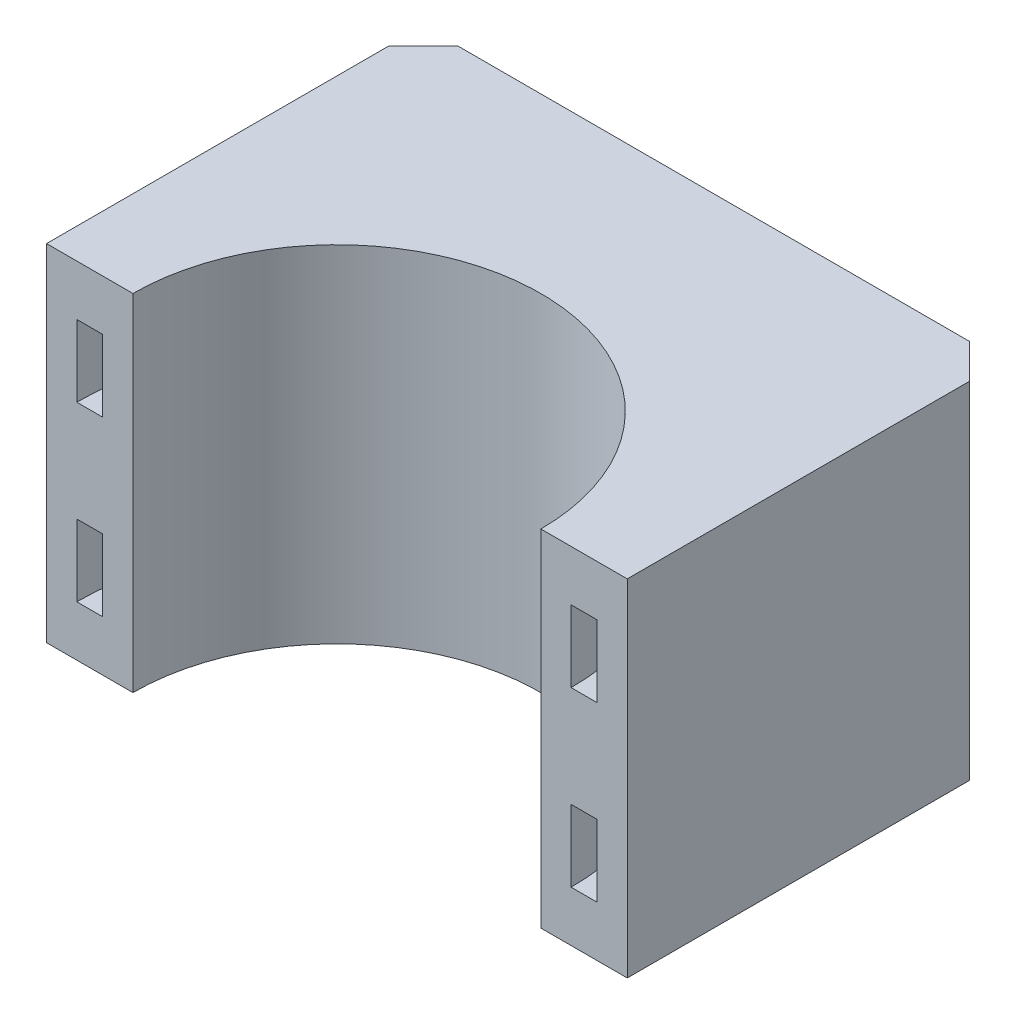
SolidWorks part; units mm, degrees
ref_plane "Front Plane" through (0, 0, 0) normal (0, 0, 1) x (1, 0, 0)
ref_plane "Top Plane" through (0, 0, 0) normal (0, 1, 0) x (1, 0, 0)
ref_plane "Right Plane" through (0, 0, 0) normal (1, 0, 0) x (0, 0, -1)
sketch "Sketch1" plane through (0, 0, 0) normal (0, 1, 0) x (1, 0, 0)
  line L0 (-11.8, 0) -> (-16.8, 0)
  line L1 (-16.8, 0) -> (-16.8, 21.8)
  line L2 (-16.8, 21.8) -> (16.8, 21.8)
  line L3 (16.8, 21.8) -> (16.8, 0)
  line L4 (16.8, 0) -> (11.8, 0)
  arc A0 (11.8, 0) -> (-11.8, 0) centre (0, 0) ccw
  point P7 (0, 11.8)
  dimension "D1" = 11.8
  dimension "D2" = 5
  dimension "D3" = 10
extrude "Boss-Extrude1" add sketch "Sketch1" along normal mid plane 20
sketch "Sketch2" plane through (0, 0, 0) normal (0, 0, 1) x (1, 0, 0)
  line L0 (0, 0) -> (0, -50000) construction
  line L1 (0, 0) -> (14.3, 0) construction
  line L2 (14.3, 5) -> (14.3, -5) construction
  line L3 (16.8, 0) -> (11.8, 0) construction
  line L5 (13.55, 7.075) -> (15.05, 7.075)
  line L6 (13.55, 7.075) -> (13.55, 2.925)
  line L7 (13.55, 2.925) -> (15.05, 2.925)
  line L8 (15.05, 7.075) -> (15.05, 2.925)
  line L9 (13.55, 7.075) -> (15.05, 2.925) construction
  line L10 (13.55, 2.925) -> (15.05, 7.075) construction
  line L11 (13.55, -2.925) -> (15.05, -2.925)
  line L12 (13.55, -2.925) -> (13.55, -7.075)
  line L13 (13.55, -7.075) -> (15.05, -7.075)
  line L14 (15.05, -2.925) -> (15.05, -7.075)
  line L15 (13.55, -2.925) -> (15.05, -7.075) construction
  line L16 (13.55, -7.075) -> (15.05, -2.925) construction
  point P8 (14.3, 0)
  dimension "D1" = 4.15
  dimension "D2" = 1.5
  dimension "D3" = 10
revolve "Cut-Revolve1" cut sketch "Sketch2" angle 360 about L0
sketch "Sketch3" plane through (0, 0, -21.8) normal (0, 0, -1) x (-1, 0, 0)
  line L1 (-11.8, 5) -> (11.8, 5)
  line L2 (-11.8, 5) -> (-11.8, -5)
  line L3 (-11.8, -5) -> (11.8, -5)
  line L4 (11.8, 5) -> (11.8, -5)
  line L5 (-11.8, 5) -> (11.8, -5) construction
  line L6 (-11.8, -5) -> (11.8, 5) construction
  point P0 (0, 0)
  point P7 (11.8, -5)
  point P8 (11.8, 5)
  point P9 (-11.8, 5)
  point P10 (-11.8, -5)
  dimension "D1" = 10
  dimension "D2" = 23.6
hole_wizard "Tap Drill for M3x0.5 Tap1" positions "Sketch3" profile "Sketch5" hole size "M3x0.5" standard "ANSI Metric"
sketch "Sketch5" plane through (0, 0, -21.8) normal (1, 0, 0) x (0, 1, 0)
  line L0 (0, 0) -> (0, 9)
  line L1 (0, 9) -> (1.25, 8.2489)
  line L2 (1.25, 8.2489) -> (1.25, 0)
  line L5 (1.25, 0) -> (0, 0)
  line L10 (0, 9) -> (-1.25, 8.2489) construction
  line L11 (0, -6.35) -> (0, 107.95) construction
  dimension "Hole Dia." = 2.5
  dimension "Hole Depth" = 9
  dimension "Drill Angle" = 118
chamfer "Chamfer1" distance 2 angle 45 2 edges at (-16.8, 0, -21.8) (16.8, 0, -21.8)
